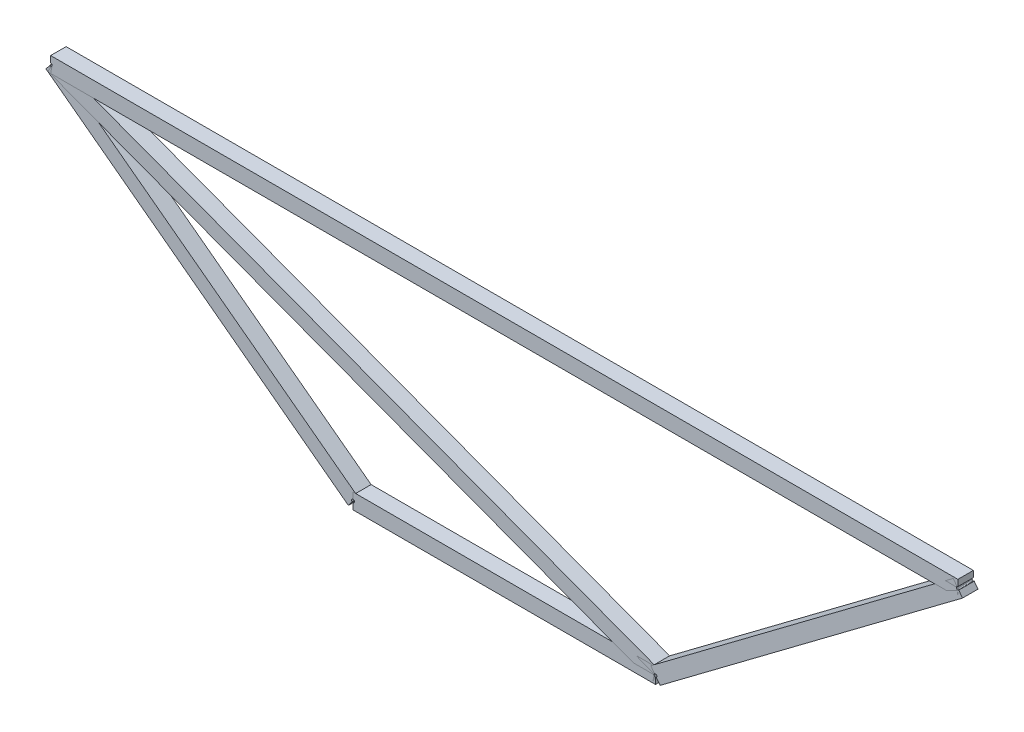
SolidWorks part; units mm, degrees
material "A500 Steel"
ref_plane "Front Plane" through (0, 0, 0) normal (0, 0, 1) x (1, 0, 0)
ref_plane "Top Plane" through (0, 0, 0) normal (0, 1, 0) x (1, 0, 0)
ref_plane "Right Plane" through (0, 0, 0) normal (1, 0, 0) x (0, 0, -1)
sketch "Sketch2" plane through (0, 0, 0) normal (0, 0, 1) x (1, 0, 0)
  line L0 (0, 0) -> (400, 0)
  line L1 (400, 0) -> (800, 0) construction
  line L2 (0, 0) -> (-400, 0) construction
  line L3 (0, 0) -> (-400, 300)
  line L4 (200, 0) -> (200, 560.886) construction
  line L5 (400, 0) -> (800, 300)
  line L6 (-400, 300) -> (800, 300)
  line L7 (-400, 300) -> (400, 0)
  point P3 (0, 0)
  point P10 (800, 300)
  point P11 (-400, 300)
  point P12 (0, 0)
  point P13 (400, 0)
  point P14 (0, 0)
  dimension "D1" = 400
  dimension "D2" = 500
  dimension "D3" = 500
ref_plane "Plane1" through (0, 0, 0) normal (-0.8, 0.6, 0) x (-0.6, -0.8, 0)
sketch "Sketch123" plane through (0, 0, 0) normal (0, 0, 1) x (1, 0, 0)
  line L0 (0, 0) -> (400, 0) construction
  line L1 (0, 0) -> (400, 0)
sketch "Sketch124" plane through (0, 0, 0) normal (0, 0, 1) x (1, 0, 0)
  line L0 (0, 0) -> (-400, 300) construction
  line L1 (0, 0) -> (-400, 300)
sketch "Sketch125" plane through (0, 0, 0) normal (0, 0, 1) x (1, 0, 0)
  line L0 (-400, 300) -> (400, 0) construction
  line L1 (-400, 300) -> (400, 0)
sketch "Sketch126" plane through (0, 0, 0) normal (0, 0, 1) x (1, 0, 0)
  line L0 (400, 0) -> (800, 300) construction
  line L1 (400, 0) -> (800, 300)
sketch "Sketch128" plane through (0, 0, 0) normal (0, 0, 1) x (1, 0, 0)
  line L0 (-400, 300) -> (800, 300) construction
  line L1 (-400, 300) -> (800, 300)
sketch "Sketch129" plane through (0, 0, 0) normal (1, 0, 0) x (0, 0, -1)
  line L1 (-10.2378, 289.7622) -> (10.2378, 289.7622)
  line L2 (-10.2378, 289.7622) -> (-10.2378, 310.2378)
  line L3 (-10.2378, 310.2378) -> (10.2378, 310.2378)
  line L4 (10.2378, 289.7622) -> (10.2378, 310.2378)
  line L5 (-10.2378, 289.7622) -> (10.2378, 310.2378) construction
  line L6 (-10.2378, 310.2378) -> (10.2378, 289.7622) construction
  point P0 (0, 300)
  dimension "D1" = 20.4756
sketch "Sketch130" plane through (0, 0, 0) normal (1, 0, 0) x (0, 0, -1)
  line L1 (-10.2378, -10.2378) -> (10.2378, -10.2378)
  line L2 (-10.2378, -10.2378) -> (-10.2378, 10.2378)
  line L3 (-10.2378, 10.2378) -> (10.2378, 10.2378)
  line L4 (10.2378, -10.2378) -> (10.2378, 10.2378)
  line L5 (-10.2378, -10.2378) -> (10.2378, 10.2378) construction
  line L6 (-10.2378, 10.2378) -> (10.2378, -10.2378) construction
  point P0 (0, 0)
  dimension "D1" = 20.4756
ref_plane "Plane3" through (800, 300, 0) normal (-0.8, -0.6, 0) x (0, 0, 1)
sketch "Sketch131" plane through (800, 300, 0) normal (-0.8, -0.6, 0) x (0, 0, 1)
  line L1 (-10.2378, -10.2378) -> (10.2378, -10.2378)
  line L2 (-10.2378, -10.2378) -> (-10.2378, 10.2378)
  line L3 (-10.2378, 10.2378) -> (10.2378, 10.2378)
  line L4 (10.2378, -10.2378) -> (10.2378, 10.2378)
  line L5 (-10.2378, -10.2378) -> (10.2378, 10.2378) construction
  line L6 (-10.2378, 10.2378) -> (10.2378, -10.2378) construction
  point P0 (0, 0)
  dimension "D1" = 20.4756
ref_plane "Plane4" through (-400, 300, 0) normal (-0.8, 0.6, 0) x (0, 0, 1)
sketch "Sketch134" plane through (-400, 300, 0) normal (-0.8, 0.6, 0) x (0, 0, 1)
  line L1 (-10.2378, -10.2378) -> (10.2378, -10.2378)
  line L2 (-10.2378, -10.2378) -> (-10.2378, 10.2378)
  line L3 (-10.2378, 10.2378) -> (10.2378, 10.2378)
  line L4 (10.2378, -10.2378) -> (10.2378, 10.2378)
  line L5 (-10.2378, -10.2378) -> (10.2378, 10.2378) construction
  line L6 (-10.2378, 10.2378) -> (10.2378, -10.2378) construction
  point P0 (0, 0)
  dimension "D1" = 20.4756
ref_plane "Plane5" through (400, 0, 0) normal (0.9363, -0.3511, 0) x (0, 0, -1)
sketch "Sketch135" plane through (400, 0, 0) normal (0.9363, -0.3511, 0) x (0, 0, -1)
  line L1 (-10.2378, -10.2378) -> (10.2378, -10.2378)
  line L2 (-10.2378, -10.2378) -> (-10.2378, 10.2378)
  line L3 (-10.2378, 10.2378) -> (10.2378, 10.2378)
  line L4 (10.2378, -10.2378) -> (10.2378, 10.2378)
  line L5 (-10.2378, -10.2378) -> (10.2378, 10.2378) construction
  line L6 (-10.2378, 10.2378) -> (10.2378, -10.2378) construction
  point P0 (0, 0)
  dimension "D1" = 20.4756
sweep "Sweep3" add profiles "Sketch129" path "Sketch2"
sweep "Sweep4" add profiles "Sketch130" path "Sketch123"
sweep "Sweep5" add profiles "Sketch131" path "Sketch126"
sweep "Sweep6" add profiles "Sketch135" path "Sketch125"
sweep "Sweep7" add profiles "Sketch134" path "Sketch124"
sketch "Sketch154" plane through (0, 0, -10.2378) normal (0, 0, -1) x (-1, 0, 0)
  line L0 (393.8573, 308.1902) -> (406.1427, 291.8098) construction
  circle A0 centre (-800, 300) radius 1.9029
  circle A1 centre (-400, 0) radius 1.9029
  circle A2 centre (0, 0) radius 1.9029
  circle A3 centre (400, 300) radius 1.9029
  dimension "D1" = 3.8058
extrude "Cut-Extrude10" cut sketch "Sketch154" against normal through all both and the other way through all
sketch "Sketch137" plane through (0, 0, 0) normal (0, 0, 1) x (1, 0, 0)
  circle A0 centre (-400, 300) radius 1.9029
  circle A1 centre (800, 300) radius 1.9029
  dimension "D1" = 3.8058
